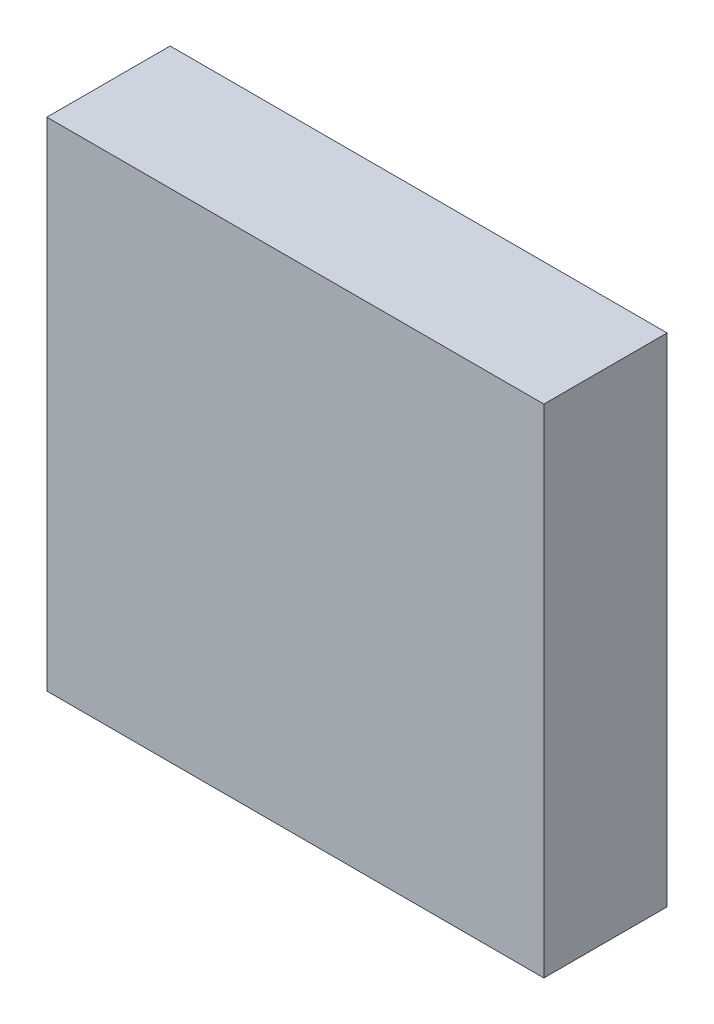
SolidWorks part; units mm, degrees
ref_plane "Front Plane" through (0, 0, 0) normal (0, 0, 1) x (1, 0, 0)
ref_plane "Top Plane" through (0, 0, 0) normal (0, 1, 0) x (1, 0, 0)
ref_plane "Right Plane" through (0, 0, 0) normal (1, 0, 0) x (0, 0, -1)
sketch "Sketch1" plane through (0, 0, 0) normal (0, 0, 1) x (1, 0, 0)
  line L0 (-2.016, 2.016) -> (2.016, 2.016)
  line L1 (2.016, 2.016) -> (2.016, -2.016)
  line L2 (2.016, -2.016) -> (-2.016, -2.016)
  line L3 (-2.016, -2.016) -> (-2.016, 2.016)
extrude "Component_Outline" add sketch "Sketch1" along normal blind 1 separate body
sketch3d "3DSketch1"
  line L0 (0, 0, 0) -> (1, 0, 0)
  line L1 (0, 0, 0) -> (0, 1, 0)
  line L2 (0, 0, 0) -> (0, 0, 1)
  point P0 (0, 0, 0)
